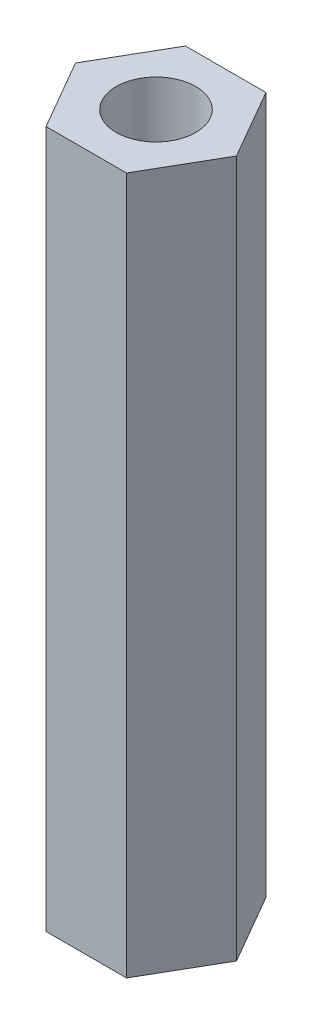
SolidWorks part; units mm, degrees
ref_plane "Front Plane" through (0, 0, 0) normal (0, 0, 1) x (1, 0, 0)
ref_plane "Top Plane" through (0, 0, 0) normal (0, 1, 0) x (1, 0, 0)
ref_plane "Right Plane" through (0, 0, 0) normal (1, 0, 0) x (0, 0, -1)
sketch "Sketch1" plane through (0, 0, 0) normal (0, 1, 0) x (1, 0, 0)
  line L1 (2.0207, 3.5) -> (-2.0207, 3.5)
  line L2 (-2.0207, 3.5) -> (-4.0415, 0)
  line L3 (-4.0415, 0) -> (-2.0207, -3.5)
  line L4 (-2.0207, -3.5) -> (2.0207, -3.5)
  line L5 (2.0207, -3.5) -> (4.0415, 0)
  line L6 (4.0415, 0) -> (2.0207, 3.5)
  circle A0 centre (0, 0) radius 3.5 construction
  circle A1 centre (0, 0) radius 2
  dimension "D1" = 4
  dimension "D2" = 7
extrude "Boss-Extrude1" add sketch "Sketch1" along normal blind 35
